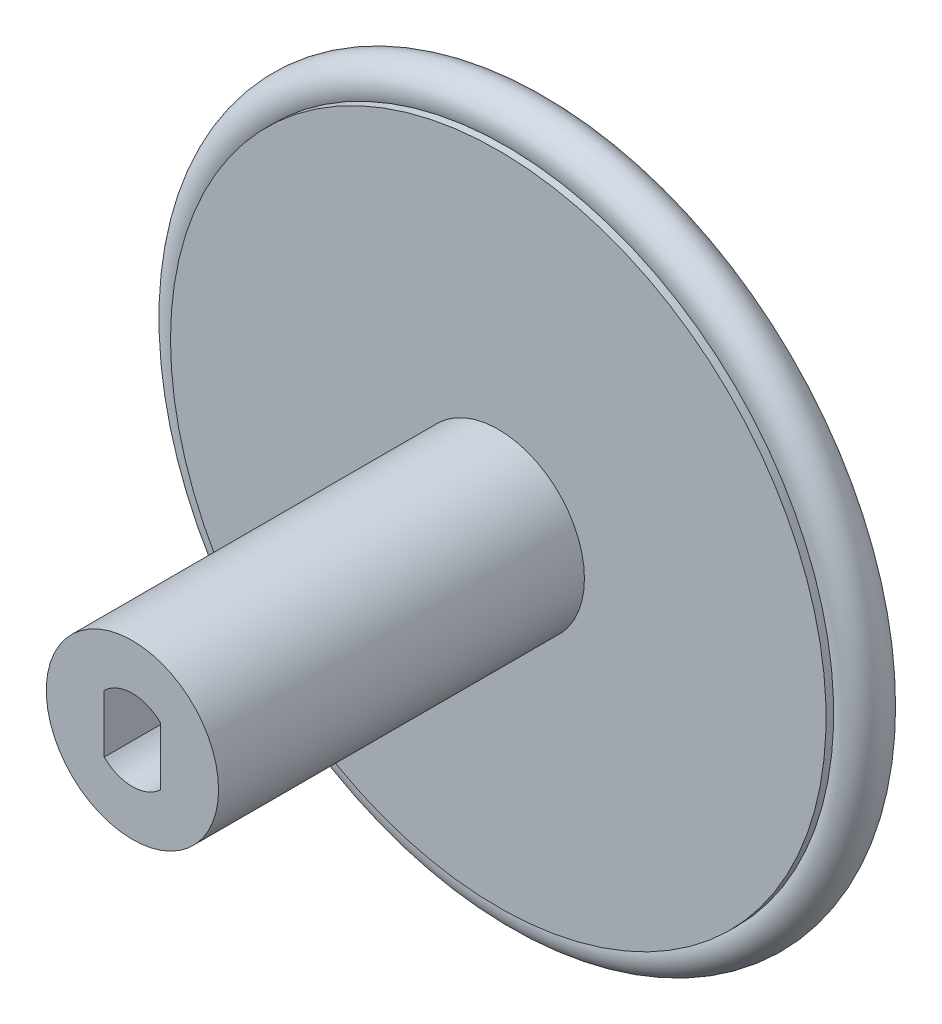
SolidWorks part; units mm, degrees
ref_plane "Alzado" through (0, 0, 0) normal (0, 0, 1) x (1, 0, 0)
ref_plane "Planta" through (0, 0, 0) normal (0, 1, 0) x (1, 0, 0)
ref_plane "Vista lateral" through (0, 0, 0) normal (1, 0, 0) x (0, 0, -1)
sketch "Croquis1" plane through (0, 0, 0) normal (1, 0, 0) x (0, 0, -1)
  line L0 (6.2271, 0) -> (-6.2271, 0) construction
  line L1 (0, 21.5) -> (0, -21.5) construction
  line L2 (-1.9, 0) -> (-1.9, 21.5)
  line L3 (-1.9, 21.5) -> (-1.4, 21.5)
  line L4 (-1.4, 21.5) -> (-0.5, 19.0002)
  line L5 (-0.5, 19.0002) -> (0.5, 19.0002)
  line L6 (1.4, 21.5) -> (0.5, 19.0002)
  line L7 (1.9, 21.5) -> (1.4, 21.5)
  line L8 (1.9, 0) -> (1.9, 21.5)
  line L9 (-1.9, 0) -> (1.9, 0)
  point P4 (0, 0)
  point P8 (0, 0)
  point P18 (0, 19.0002)
  dimension "D1" = 43
  dimension "D2" = 3.8
  dimension "D3" = 19.8
  dimension "D4" = 1
  dimension "D5" = 0.5
  dimension "D6" = 2.6569
revolve "Revolución1" add sketch "Croquis1" angle 360 about L0
sketch "Croquis3" plane through (0, 0, 1.9) normal (0, 0, 1) x (1, 0, 0)
  line L1 (-1.85, 1.8974) -> (1.85, 1.8974) construction
  line L2 (-1.85, 1.8974) -> (-1.85, -1.8974)
  line L3 (-1.85, -1.8974) -> (1.85, -1.8974) construction
  line L4 (1.85, 1.8974) -> (1.85, -1.8974)
  line L5 (-1.85, 1.8974) -> (1.85, -1.8974) construction
  line L6 (-1.85, -1.8974) -> (1.85, 1.8974) construction
  circle A0 centre (0, 0) radius 2.65 construction
  arc A1 (-1.85, 1.8974) -> (1.85, 1.8974) centre (0, 0) cw
  arc A2 (-1.85, -1.8974) -> (1.85, -1.8974) centre (0, 0) ccw
  circle A3 centre (0, 0) radius 5.65
  dimension "D1" = 5.3
  dimension "D4" = 11.3
  dimension "D2" = 3.7
  dimension "D3" = 3
extrude "Saliente-Extruir2" add sketch "Croquis3" along normal blind 24
sketch "Croquis4" plane through (0, 0, 25.9) normal (0, 0, 1) x (1, 0, 0)
  line L2 (-1.85, 1.8974) -> (-1.85, -1.8974)
  line L3 (1.85, -1.8974) -> (1.85, 1.8974)
  line L4 (-1.85, 1.8974) -> (-1.85, -1.8974)
  line L5 (1.85, -1.8974) -> (1.85, 1.8974)
  arc A2 (-1.85, -1.8974) -> (1.85, -1.8974) centre (0, 0) ccw
  arc A3 (1.85, 1.8974) -> (-1.85, 1.8974) centre (0, 0) ccw
  arc A4 (-1.85, -1.8974) -> (1.85, -1.8974) centre (0, 0) ccw
  arc A5 (1.85, 1.8974) -> (-1.85, 1.8974) centre (0, 0) ccw
  dimension "D1" = 0
extrude "Saliente-Extruir3" add sketch "Croquis4" against normal up to next from offset 5 offset against normal yes
sketch "Croquis5" plane through (0, 0, 0) normal (1, 0, 0) x (0, 0, -1)
  line L0 (-0.5, 19.0002) -> (-1.4, 21.5) construction
  line L1 (-9.0932, 0) -> (9.0932, 0) construction
  circle A0 centre (0, 22.0396) radius 1.5
  point P9 (0, 0)
  dimension "D1" = 3
revolve "Revolución2" add sketch "Croquis5" angle 360 about L1
